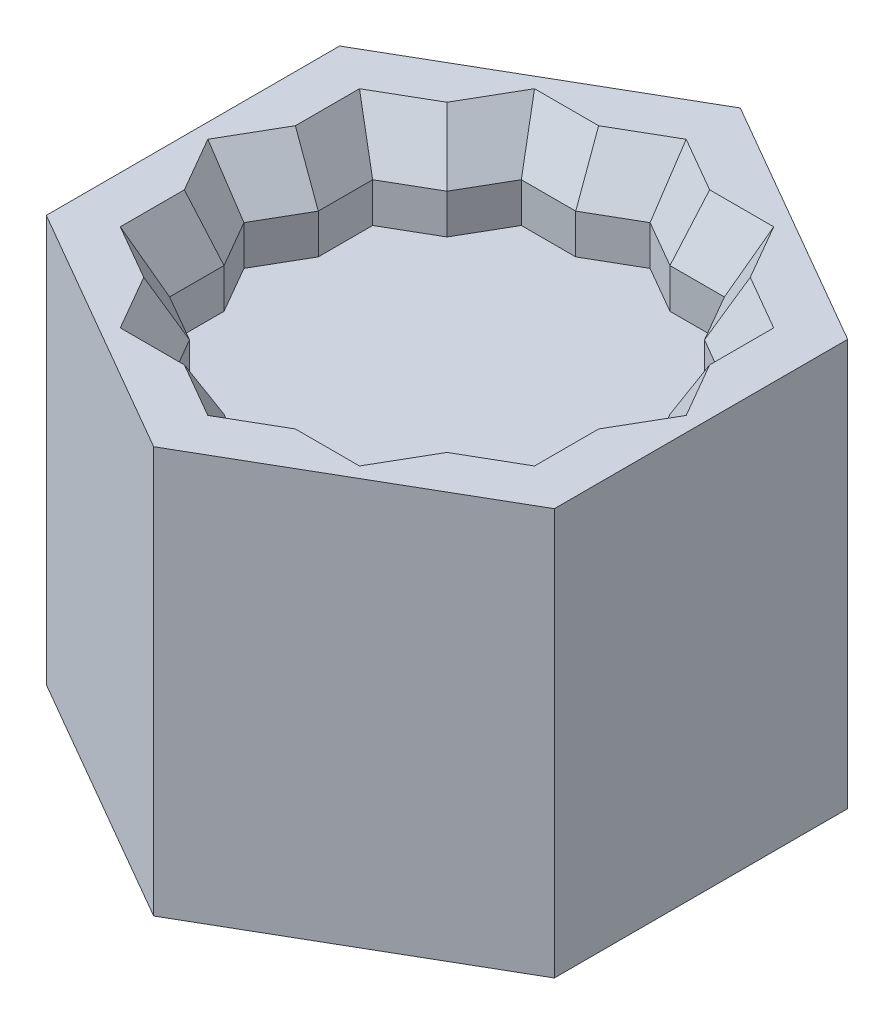
SolidWorks part; units mm, degrees
ref_plane "Front Plane" through (0, 0, 0) normal (0, 0, 1) x (1, 0, 0)
ref_plane "Top Plane" through (0, 0, 0) normal (0, 1, 0) x (1, 0, 0)
ref_plane "Right Plane" through (0, 0, 0) normal (1, 0, 0) x (0, 0, -1)
sketch "Sketch1" plane through (0, 0, 0) normal (0, 1, 0) x (1, 0, 0)
  line L1 (11.25, 6.4952) -> (0, 12.9904)
  line L2 (0, 12.9904) -> (-11.25, 6.4952)
  line L3 (-11.25, 6.4952) -> (-11.25, -6.4952)
  line L4 (-11.25, -6.4952) -> (0, -12.9904)
  line L5 (0, -12.9904) -> (11.25, -6.4952)
  line L6 (11.25, -6.4952) -> (11.25, 6.4952)
  line L7 (16.25, 9.3819) -> (0, 18.7639)
  line L8 (0, 18.7639) -> (-16.25, 9.3819)
  line L9 (-16.25, 9.3819) -> (-16.25, -9.3819)
  line L10 (-16.25, -9.3819) -> (0, -18.7639)
  line L11 (0, -18.7639) -> (16.25, -9.3819)
  line L12 (16.25, -9.3819) -> (16.25, 9.3819)
  circle A0 centre (0, 0) radius 11.25 construction
  circle A1 centre (0, 0) radius 16.25 construction
  dimension "D1" = 5
  dimension "D2" = 22.5
extrude "Boss-Extrude1" add sketch "Sketch1" along normal blind 6
sketch "Sketch5" plane through (0, 0, 0) normal (0, -1, 0) x (1, 0, 0)
  line L0 (-16.25, -9.3819) -> (-16.25, 9.3819) construction
  line L1 (16.25, 9.3819) -> (0, 18.7639)
  line L2 (0, 18.7639) -> (-16.25, 9.3819)
  line L3 (-16.25, 9.3819) -> (-16.25, -9.3819)
  line L4 (-16.25, -9.3819) -> (0, -18.7639)
  line L5 (0, -18.7639) -> (16.25, -9.3819)
  line L6 (16.25, -9.3819) -> (16.25, 9.3819)
  circle A0 centre (0, 0) radius 16.25 construction
extrude "Boss-Extrude4" add sketch "Sketch5" along normal blind 20
sketch "Sketch6" plane through (0, -20, 0) normal (0, -1, 0) x (1, 0, 0)
  line L0 (-2.4989, 1.66) -> (-2.4989, -1.66) construction
  line L1 (-2.6181, 1.66) -> (-2.6181, -1.66)
  circle A0 centre (0, 0) radius 3 construction
  arc A1 (-2.6181, -1.66) -> (-2.6181, 1.66) centre (0, 0) ccw
  dimension "D1" = 6
  dimension "D3" = 6.2
  dimension "D2" = 3.32
  dimension "D4" = 3.32
extrude "Cut-Extrude2" cut sketch "Sketch6" against normal blind 15 contours L1 A1
sketch "Sketch7" plane through (0, 6, 0) normal (0, 1, 0) x (1, 0, 0)
  line L0 (0, 0) -> (-5.625, 9.7428) construction
  line L1 (0, 12.9904) -> (-11.25, 6.4952) construction
  line L3 (-6.4952, 11.25) -> (-12.9904, 0)
  line L4 (-12.9904, 0) -> (-6.4952, -11.25)
  line L5 (-6.4952, -11.25) -> (6.4952, -11.25)
  line L6 (6.4952, -11.25) -> (12.9904, 0)
  line L7 (12.9904, 0) -> (6.4952, 11.25)
  line L8 (6.4952, 11.25) -> (-6.4952, 11.25)
  circle A0 centre (0, 0) radius 11.25 construction
  point P5 (0, 0)
  dimension "D1" = 22.5
extrude "Cut-Extrude3" cut sketch "Sketch7" against normal blind 6
chamfer "Chamfer2" distance 2 angle 60 24 edges at (-9.7428, 6, -7.3654) (-11.25, 6, -4.7548) (-12.1202, 6, -1.5072) (-12.1202, 6, 1.5072) (-11.25, 6, 4.7548) (-9.7428, 6, 7.3654) (-7.3654, 6, 9.7428) (-4.7548, 6, 11.25) (-1.5072, 6, 12.1202) (1.5072, 6, 12.1202) (4.7548, 6, 11.25) (7.3654, 6, 9.7428) (9.7428, 6, 7.3654) (11.25, 6, 4.7548) (12.1202, 6, 1.5072) (12.1202, 6, -1.5072) (11.25, 6, -4.7548) (9.7428, 6, -7.3654) (7.3654, 6, -9.7428) (4.7548, 6, -11.25) (1.5072, 6, -12.1202) (-1.5072, 6, -12.1202) (-7.3654, 6, -9.7428) (-4.7548, 6, -11.25)
